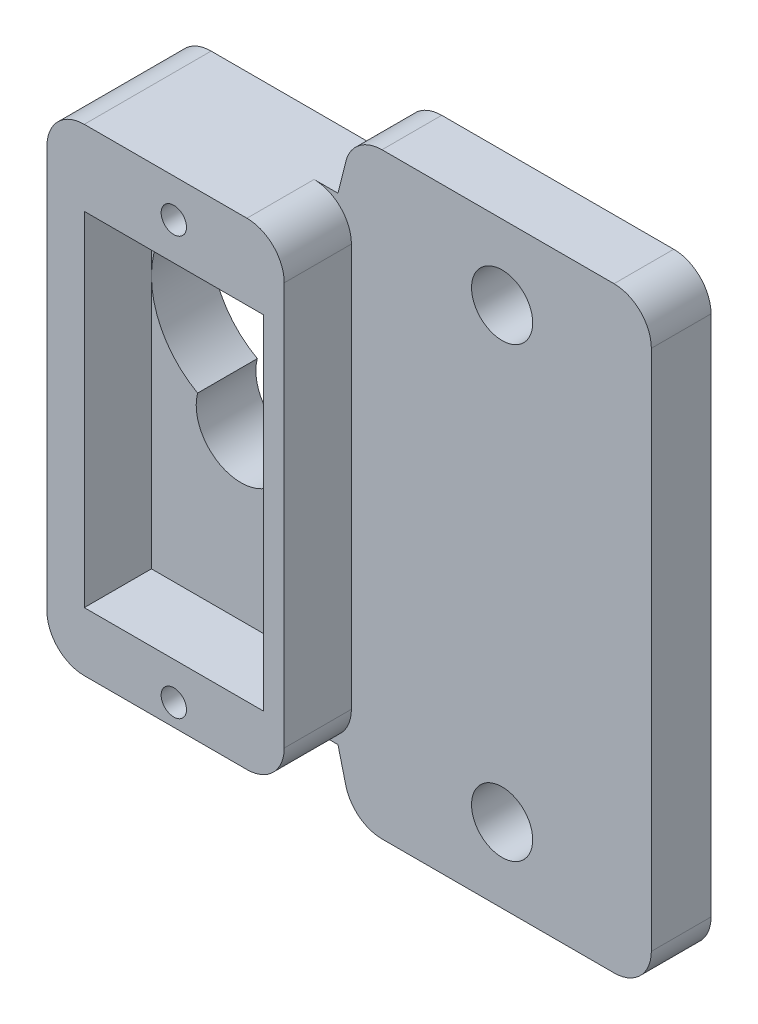
SolidWorks part; units mm, degrees
ref_plane "Plan de face" through (0, 0, 0) normal (0, 0, 1) x (1, 0, 0)
ref_plane "Plan de dessus" through (0, 0, 0) normal (0, 1, 0) x (1, 0, 0)
ref_plane "Plan de droite" through (0, 0, 0) normal (1, 0, 0) x (0, 0, -1)
sketch "Esquisse1" plane through (0, 0, 0) normal (0, 0, 1) x (1, 0, 0)
  line L0 (0, 19.6765) -> (0, -23.203) construction
  line L1 (-40.2718, 0) -> (44.7659, 0) construction
  line L2 (0, 20) -> (20, 20)
  line L3 (20, 20) -> (20, -20)
  line L4 (20, -20) -> (0, -20)
  line L5 (0, -20) -> (-16, -20) construction
  line L6 (-16, -20) -> (-16, 20) construction
  line L7 (-16, 20) -> (0, 20) construction
  line L8 (-7.5, 20) -> (-7.5, -20) construction
  line L9 (10, 20) -> (10, -20) construction
  line L10 (0, 20) -> (0, 16) construction
  line L11 (0, 16) -> (-16, 16) construction
  line L12 (-16, 16) -> (-16, -16)
  line L13 (0, -20) -> (0, -16) construction
  line L14 (0, -16) -> (-16, -16) construction
  line L15 (0, 20) -> (-1, 16)
  line L16 (-1, 16) -> (-16, 16)
  line L17 (-1, -16) -> (-16, -16)
  line L18 (0, -20) -> (-1, -16)
  circle A0 centre (-7.5, 4.95) radius 6 construction
  circle A1 centre (10, 15) radius 2.05
  circle A2 centre (10, -15) radius 2.05
  arc A3 (-10.4047, -0.3) -> (-4.5953, -0.3) centre (-7.5, -1.05) ccw construction
  arc A4 (-10.4047, -0.3) -> (-4.5953, -0.3) centre (-7.5, 4.95) cw
  arc A5 (-10.4047, -0.3) -> (-4.5953, -0.3) centre (-7.5, -1.05) ccw
  point P30 (-16, 0)
  dimension "D4" = 12
  dimension "D5" = 3
  dimension "D7" = 8.5
  dimension "D9" = 4.1
  dimension "D1" = 20
  dimension "D2" = 40
  dimension "D3" = 7.5
  dimension "D6" = 4.95
  dimension "D8" = 15
  dimension "D10" = 16
  dimension "D11" = 1
extrude "Boss.-Extru.1" add sketch "Esquisse1" along normal blind 4 contours L7 L6 L5 L4 L3 L2 A5 A4 A1 A2
sketch "Esquisse2" plane through (0, 0, 4) normal (0, 0, 1) x (1, 0, 0)
  line L0 (-7.5, 16.6119) -> (-7.5, -16.6119) construction
  line L1 (-0.1, 13.5) -> (-0.1, -13.5)
  line L2 (-1.5, -12.05) -> (-13.5, -12.05)
  line L3 (-1.5, -12.05) -> (-1.5, 10.95)
  line L4 (20, 20) -> (0, 20)
  line L5 (-1, -16) -> (0, -20)
  line L6 (0, -20) -> (20, -20)
  line L7 (20, -20) -> (20, 20)
  line L8 (20, 20) -> (0, 20)
  line L10 (0, -20) -> (20, -20)
  line L11 (20, -20) -> (20, 20)
  line L12 (-1.5, 10.95) -> (-13.5, 10.95)
  line L13 (-13.5, -12.05) -> (-13.5, 10.95)
  line L14 (-1.5, -12.05) -> (-13.5, 10.95) construction
  line L15 (-1.5, 10.95) -> (-13.5, -12.05) construction
  line L21 (-0.1, -16) -> (-1, -16)
  line L23 (-2.6, 16) -> (-16, 16)
  line L24 (-16, -16) -> (-2.6, -16)
  line L28 (-1, -16) -> (0, -20)
  line L30 (0, 20) -> (-1, 16)
  line L32 (0, 20) -> (-1, 16)
  line L34 (-1, 16) -> (-16, 16)
  line L36 (-16, 16) -> (-16, -16)
  line L37 (-16, 16) -> (-16, -16)
  line L38 (-1, 16) -> (-16, 16)
  line L39 (-16, -16) -> (-1, -16)
  line L40 (-16, -16) -> (-1, -16)
  arc A0 (-10.4047, -0.3) -> (-4.5953, -0.3) centre (-7.5, -1.05) ccw construction
  arc A1 (-4.5953, -0.3) -> (-10.4047, -0.3) centre (-7.5, 4.95) ccw construction
  arc A2 (-10.4047, -0.3) -> (-4.5953, -0.3) centre (-7.5, -1.05) ccw
  arc A3 (-4.5953, -0.3) -> (-10.4047, -0.3) centre (-7.5, 4.95) ccw
  arc A4 (-0.1, -13.5) -> (-2.6, -16) centre (-2.6, -13.5) cw
  arc A5 (-0.1, 13.5) -> (-2.6, 16) centre (-2.6, 13.5) ccw
  point P10 (-7.5, -0.55)
  point P15 (-7.5, -0.55)
  dimension "D4" = 2.5
  dimension "D5" = 2.5
  dimension "D2" = 23
  dimension "D3" = 1.4
  dimension "D1" = 0
extrude "Boss.-Extru.2" add sketch "Esquisse2" along normal blind 4.5
sketch "Esquisse3" plane through (0, 0, 8.5) normal (0, 0, 1) x (1, 0, 0)
  line L0 (-7.5, 37.9) -> (-7.5, -16) construction
  line L1 (-1.5, 10.95) -> (-7.5, 10.95) construction
  line L2 (-1.5, -12.05) -> (-13.5, -12.05) construction
  line L4 (-0.1, -13.5) -> (-0.1, 13.5)
  line L5 (-2.6, 16) -> (-16, 16)
  line L12 (-7.5, 10.95) -> (-13.5, 10.95) construction
  line L13 (-1.5, -12.05) -> (-13.5, -12.05) construction
  line L14 (-7.5, 10.95) -> (-13.5, 10.95)
  line L16 (-16, 16) -> (-16, -16)
  line L18 (-16, 16) -> (-16, -16)
  line L19 (-2.6, 16) -> (-16, 16)
  line L21 (-16, -16) -> (-2.6, -16)
  line L22 (-16, -16) -> (-2.6, -16)
  line L24 (-1.5, -12.05) -> (-13.5, -12.05)
  line L25 (-1.5, 10.95) -> (-7.5, 10.95)
  line L34 (-0.1, -13.5) -> (-0.1, 13.5)
  circle A0 centre (-7.5, 13.45) radius 0.85
  circle A1 centre (-7.5, -14.55) radius 0.85
  arc A2 (-0.1, -13.5) -> (-2.6, -16) centre (-2.6, -13.5) cw
  arc A3 (-0.1, 13.5) -> (-2.6, 16) centre (-2.6, 13.5) ccw
  arc A6 (-0.1, 13.5) -> (-2.6, 16) centre (-2.6, 13.5) ccw
  arc A7 (-0.1, 13.5) -> (-2.6, 16) centre (-2.6, 13.5) ccw
  arc A8 (-2.6, -16) -> (-0.1, -13.5) centre (-2.6, -13.5) ccw
  arc A9 (-2.6, -16) -> (-0.1, -13.5) centre (-2.6, -13.5) ccw
  dimension "D2" = 2.5
  dimension "D4" = 1.7
  dimension "D5" = 2.5
  dimension "D3" = 2.5
  dimension "D1" = 0
extrude "Enlèv. mat.-Extru.1" cut sketch "Esquisse3" against normal blind 8 contours A0 | A1
fillet "Congé1" radius 2.5 6 edges at (20, 20, 2) (20, -20, 2) (0, 20, 2) (0, -20, 2) (-16, -16, 4.25) (-16, 16, 4.25)
